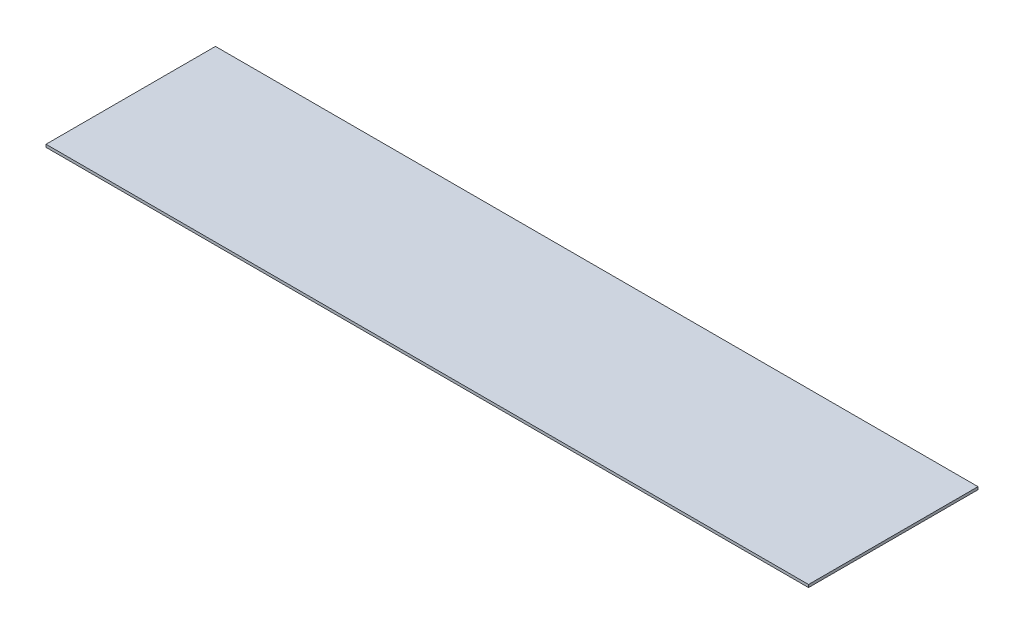
SolidWorks part; units mm, degrees
ref_plane "Front Plane" through (0, 0, 0) normal (0, 0, 1) x (1, 0, 0)
ref_plane "Top Plane" through (0, 0, 0) normal (0, 1, 0) x (1, 0, 0)
ref_plane "Right Plane" through (0, 0, 0) normal (1, 0, 0) x (0, 0, -1)
sketch "Sketch1" plane through (0, 0, 0) normal (0, 1, 0) x (1, 0, 0)
  line L1 (-893.7625, -198.628) -> (893.7625, -198.628)
  line L2 (-893.7625, -198.628) -> (-893.7625, 198.628)
  line L3 (-893.7625, 198.628) -> (893.7625, 198.628)
  line L4 (893.7625, -198.628) -> (893.7625, 198.628)
  line L5 (-893.7625, -198.628) -> (893.7625, 198.628) construction
  line L6 (-893.7625, 198.628) -> (893.7625, -198.628) construction
  point P0 (0, 0)
  dimension "D1" = 1787.525
  dimension "D2" = 397.256
extrude "Boss-Extrude1" add sketch "Sketch1" along normal blind 6.35
